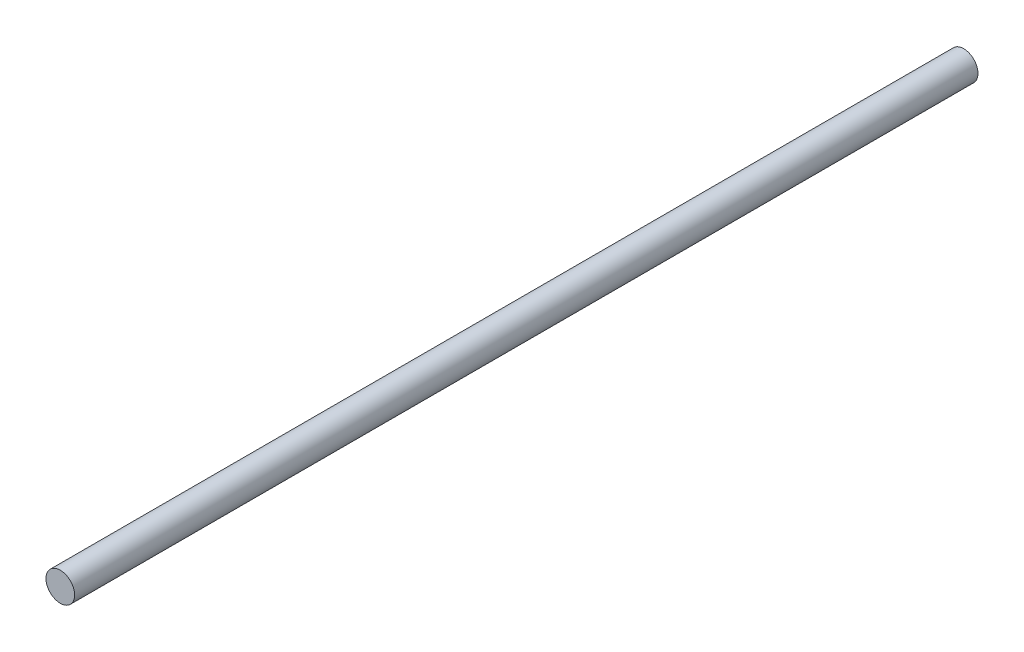
SolidWorks part; units mm, degrees
ref_plane "前视基准面" through (0, 0, 0) normal (0, 0, 1) x (1, 0, 0)
ref_plane "上视基准面" through (0, 0, 0) normal (0, 1, 0) x (1, 0, 0)
ref_plane "右视基准面" through (0, 0, 0) normal (1, 0, 0) x (0, 0, -1)
other "Configuration Table"
sketch "草图1" plane through (0, 0, 0) normal (0, 0, 1) x (1, 0, 0)
  circle A0 centre (0, 0) radius 1.5
extrude "外形" add sketch "草图1" along normal blind 94.55 from offset 0
